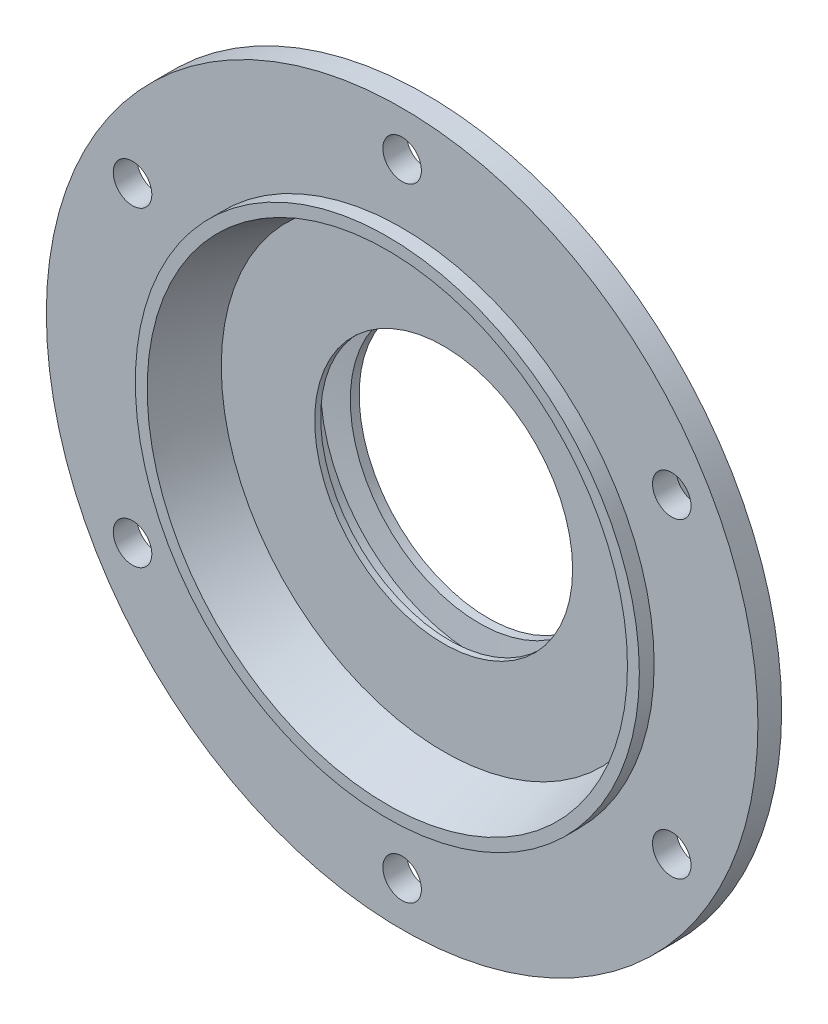
SolidWorks part; units mm, degrees
ref_plane "前视基准面" through (0, 0, 0) normal (0, 0, 1) x (1, 0, 0)
ref_plane "上视基准面" through (0, 0, 0) normal (0, 1, 0) x (1, 0, 0)
ref_plane "右视基准面" through (0, 0, 0) normal (1, 0, 0) x (0, 0, -1)
sketch "草图1" plane through (0, 0, 0) normal (1, 0, 0) x (0, 0, -1)
  line L0 (0, -1000) -> (0, 49000) construction
  line L1 (0, 43.5) -> (-3, 43.5)
  line L2 (-1000, 0) -> (49000, 0) construction
  line L3 (-3, 43.5) -> (-4, 52.5)
  line L4 (-4, 52.5) -> (-12, 52.5)
  line L5 (-12, 52.5) -> (-13, 43.5)
  line L6 (-13, 43.5) -> (-15, 43.5)
  line L7 (-8, -947.434) -> (-8, 49052.566) construction
  line L8 (-15, 43.5) -> (-15, 75)
  line L9 (-15, 75) -> (-34, 81)
  line L10 (-34, 81) -> (-34, 85)
  line L11 (-34, 85) -> (-29, 85)
  line L12 (-29, 85) -> (-29, 120)
  line L13 (-29, 120) -> (-21, 120)
  line L14 (-21, 120) -> (-21, 85)
  line L15 (-21, 85) -> (-7, 85)
  line L16 (-7, 85) -> (-7, 63)
  line L17 (-7, 63) -> (0, 63)
  line L18 (0, 63) -> (0, 43.5)
  point P25 (-8, 52.5)
  dimension "D1" = 43.5
  dimension "D2" = 8
  dimension "D3" = 10
  dimension "D6" = 52.5
  dimension "D7" = 75
  dimension "D8" = 81
  dimension "D9" = 19
  dimension "D10" = 85
  dimension "D11" = 5
  dimension "D12" = 120
  dimension "D13" = 8
  dimension "D14" = 14
  dimension "D15" = 7
  dimension "D16" = 63
  dimension "D17" = 2
revolve "旋转1" add sketch "草图1" angle 360 about L2
sketch "草图2" plane through (0, 0, 21) normal (0, 0, -1) x (-1, 0, 0)
  line L0 (0, -1000) -> (0, 49000) construction
  circle A0 centre (0, 105) radius 6.5
  dimension "D1" = 13
  dimension "D2" = 105
extrude "切除-拉伸1" cut sketch "草图2" against normal through all
pattern_circular "阵列(圆周)1" count 6 over 360 about axis through (0, 0, 0) along (0, 0, 1) of "切除-拉伸1"
